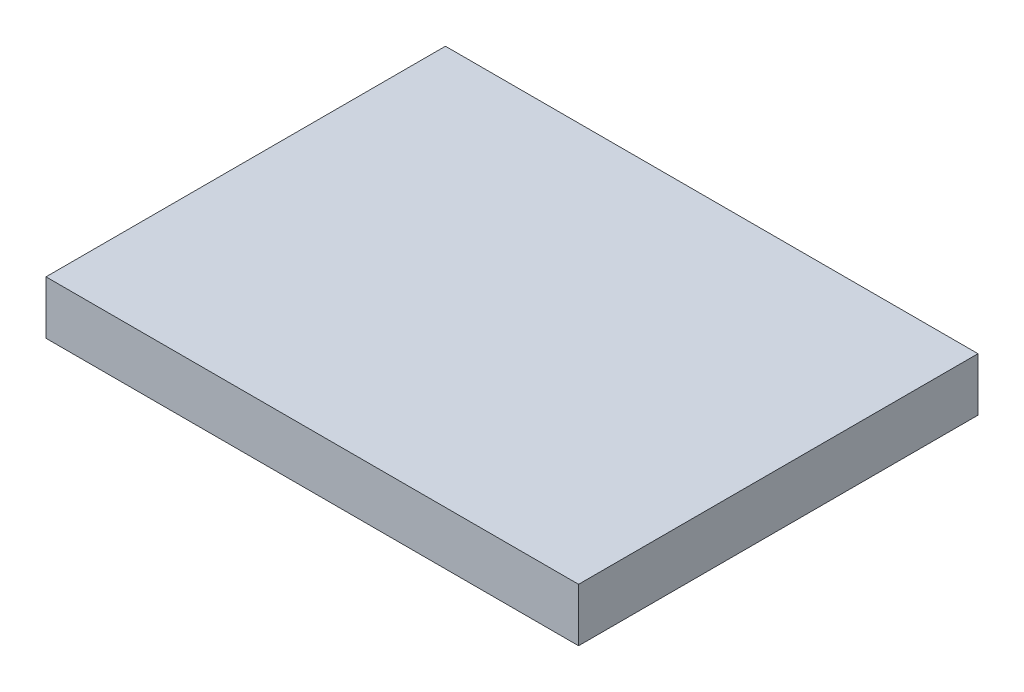
SolidWorks part; units mm, degrees
ref_plane "Front Plane" through (0, 0, 0) normal (0, 0, 1) x (1, 0, 0)
ref_plane "Top Plane" through (0, 0, 0) normal (0, 1, 0) x (1, 0, 0)
ref_plane "Right Plane" through (0, 0, 0) normal (1, 0, 0) x (0, 0, -1)
sketch "Sketch1" plane through (0, 0, 0) normal (0, 1, 0) x (1, 0, 0)
  line L1 (0, 0) -> (-40, 0)
  line L2 (0, 0) -> (0, 30)
  line L3 (0, 30) -> (-40, 30)
  line L4 (-40, 0) -> (-40, 30)
  dimension "D1" = 30
  dimension "D2" = 40
extrude "Boss-Extrude1" add sketch "Sketch1" along normal blind 4
sketch "Sketch2" plane through (0, 4, 0) normal (0, 1, 0) x (1, 0, 0)
  line L0 (0, 0) -> (0, 30) construction
  line L1 (-40, 0) -> (-30.4626, 0)
  line L2 (-40, 0) -> (-40, 8.7339)
  line L3 (-40, 8.7339) -> (-30.4626, 8.7339)
  line L4 (-30.4626, 0) -> (-30.4626, 8.7339)
  line L5 (-40, 30) -> (0, 30)
  line L6 (-40, 30) -> (-40, 24.3416)
  line L7 (-40, 24.3416) -> (0, 24.3416)
  line L8 (0, 30) -> (0, 24.3416)
  line L9 (-21.8302, 0) -> (-21.8302, 11.3818)
  line L10 (-40, 0) -> (0, 0) construction
  line L11 (-21.8302, 11.3818) -> (-26.5332, 11.3818)
  line L12 (-26.5332, 11.3818) -> (-26.5332, 19.1929)
  line L13 (-26.5332, 19.1929) -> (-9.1933, 19.1929)
  line L14 (-9.1933, 19.1929) -> (-9.1933, 11.3818)
  line L15 (-9.1933, 11.3818) -> (-17.8633, 11.3818)
  line L16 (-17.8633, 11.3818) -> (-17.8633, 4.1432)
  line L17 (-17.8633, 4.1432) -> (-10.911, 4.1432)
  line L18 (-10.911, 4.1432) -> (0, 14.4899)
  line L19 (0, 14.4899) -> (0, 0)
  line L20 (0, 0) -> (-21.8302, 0)
  line L21 (-34, 26) -> (-6, 26) construction
  line L22 (-6, 26) -> (-6, 3) construction
  line L23 (-6, 3) -> (-34, 3) construction
  line L24 (-34, 3) -> (-34, 26) construction
  circle A0 centre (-35.8659, 16.7358) radius 3.9007
  circle A1 centre (-34, 26) radius 1.75 construction
  circle A2 centre (-6, 26) radius 1.75 construction
  circle A3 centre (-6, 3) radius 1.75 construction
  circle A4 centre (-34, 3) radius 1.75 construction
  dimension "D1" = 3.5
  dimension "D2" = 28
  dimension "D3" = 23
  dimension "D4" = 3
  dimension "D5" = 6
